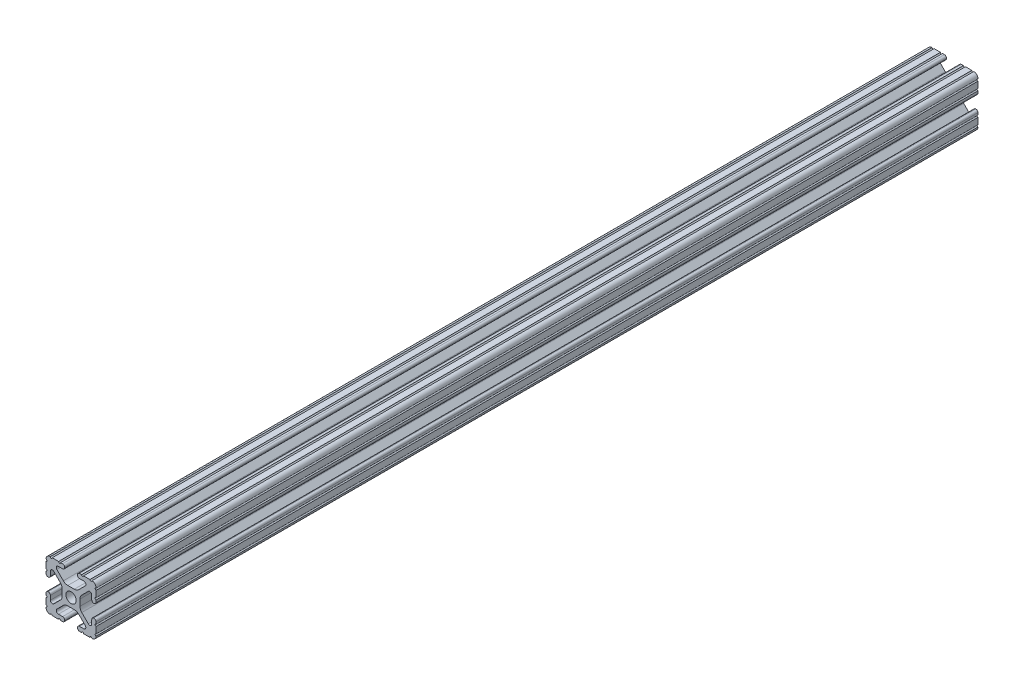
SolidWorks part; units mm, degrees
ref_plane "Front Plane" through (0, 0, 0) normal (0, 0, 1) x (1, 0, 0)
ref_plane "Top Plane" through (0, 0, 0) normal (0, 1, 0) x (1, 0, 0)
ref_plane "Right Plane" through (0, 0, 0) normal (1, 0, 0) x (0, 0, -1)
sketch "Sketch1" plane through (0, 0, 0) normal (0, 0, 1) x (1, 0, 0)
  line L88 (-7.1797, -8.6452) -> (-3.9523, -5.4237)
  line L89 (-1.7093, -4.4958) -> (1.7093, -4.4958)
  line L90 (3.9523, -5.4237) -> (7.1797, -8.6452)
  line L91 (6.4164, -10.4902) -> (4.2875, -10.4902)
  line L92 (3.2385, -11.5392) -> (3.2385, -11.651)
  line L93 (4.2875, -12.7) -> (5.3171, -12.7)
  line L94 (6.3331, -12.7) -> (9.5504, -12.7)
  line L95 (12.7, -9.5504) -> (12.7, -6.3331)
  line L96 (12.7, -5.3171) -> (12.7, -4.2875)
  line L97 (11.651, -3.2385) -> (11.5392, -3.2385)
  line L98 (10.4902, -4.2875) -> (10.4902, -6.4021)
  line L99 (8.7371, -7.1294) -> (5.441, -3.8408)
  line L100 (4.5085, -1.5932) -> (4.5085, 1.5932)
  line L101 (5.441, 3.8408) -> (8.7371, 7.1294)
  line L102 (10.4902, 6.4021) -> (10.4902, 4.2875)
  line L103 (11.5392, 3.2385) -> (11.651, 3.2385)
  line L104 (12.7, 4.2875) -> (12.7, 5.3171)
  line L105 (12.7, 6.3331) -> (12.7, 9.5504)
  line L106 (9.5504, 12.7) -> (6.3331, 12.7)
  line L107 (5.3171, 12.7) -> (4.2875, 12.7)
  line L108 (3.2385, 11.651) -> (3.2385, 11.5392)
  line L109 (4.2875, 10.4902) -> (6.4768, 10.4902)
  line L110 (7.207, 8.7244) -> (3.8983, 5.4232)
  line L111 (1.6558, 4.4958) -> (-1.6558, 4.4958)
  line L112 (-3.8983, 5.4232) -> (-7.207, 8.7244)
  line L113 (-6.4768, 10.4902) -> (-4.2875, 10.4902)
  line L114 (-3.2385, 11.5392) -> (-3.2385, 11.651)
  line L115 (-4.2875, 12.7) -> (-5.3171, 12.7)
  line L116 (-6.3331, 12.7) -> (-9.5504, 12.7)
  line L117 (-12.7, 9.5504) -> (-12.7, 6.3331)
  line L118 (-12.7, 5.3171) -> (-12.7, 4.2875)
  line L119 (-11.651, 3.2385) -> (-11.5392, 3.2385)
  line L120 (-10.4902, 4.2875) -> (-10.4902, 6.4021)
  line L121 (-8.7371, 7.1294) -> (-5.441, 3.8408)
  line L122 (-4.5085, 1.5932) -> (-4.5085, -1.5932)
  line L123 (-5.441, -3.8408) -> (-8.7371, -7.1294)
  line L124 (-10.4902, -6.4021) -> (-10.4902, -4.2875)
  line L125 (-11.5392, -3.2385) -> (-11.651, -3.2385)
  line L126 (-12.7, -4.2875) -> (-12.7, -5.3171)
  line L127 (-12.7, -6.3331) -> (-12.7, -9.5504)
  line L128 (-9.5504, -12.7) -> (-6.3331, -12.7)
  line L129 (-5.3171, -12.7) -> (-4.2875, -12.7)
  line L130 (-3.2385, -11.651) -> (-3.2385, -11.5392)
  line L131 (-4.2875, -10.4902) -> (-6.4164, -10.4902)
  circle A1 centre (0, 0) radius 2.6035
  arc A104 (-7.1797, -8.6452) -> (-6.4164, -10.4902) centre (-6.4164, -9.4098) ccw
  arc A105 (-1.7093, -4.4958) -> (-3.9523, -5.4237) centre (-1.7093, -7.6708) ccw
  arc A106 (3.9523, -5.4237) -> (1.7093, -4.4958) centre (1.7093, -7.6708) ccw
  arc A107 (6.4164, -10.4902) -> (7.1797, -8.6452) centre (6.4164, -9.4098) ccw
  arc A108 (4.2875, -10.4902) -> (3.2385, -11.5392) centre (4.2875, -11.5392) ccw
  arc A109 (3.2385, -11.651) -> (4.2875, -12.7) centre (4.2875, -11.651) ccw
  arc A110 (6.3331, -12.7) -> (5.3171, -12.7) centre (5.8251, -12.7) ccw
  arc A111 (10.5664, -12.6998) -> (9.5504, -12.7) centre (10.0584, -12.7) ccw
  arc A112 (10.5664, -12.6998) -> (12.6998, -10.5664) centre (10.5918, -10.5918) ccw
  arc A113 (12.7, -9.5504) -> (12.6998, -10.5664) centre (12.7, -10.0584) ccw
  arc A114 (12.7, -5.3171) -> (12.7, -6.3331) centre (12.7, -5.8251) ccw
  arc A115 (12.7, -4.2875) -> (11.651, -3.2385) centre (11.651, -4.2875) ccw
  arc A116 (11.5392, -3.2385) -> (10.4902, -4.2875) centre (11.5392, -4.2875) ccw
  arc A117 (8.7371, -7.1294) -> (10.4902, -6.4021) centre (9.4628, -6.4021) ccw
  arc A118 (4.5085, -1.5932) -> (5.441, -3.8408) centre (7.6835, -1.5932) ccw
  arc A119 (5.441, 3.8408) -> (4.5085, 1.5932) centre (7.6835, 1.5932) ccw
  arc A120 (10.4902, 6.4021) -> (8.7371, 7.1294) centre (9.4628, 6.4021) ccw
  arc A121 (10.4902, 4.2875) -> (11.5392, 3.2385) centre (11.5392, 4.2875) ccw
  arc A122 (11.651, 3.2385) -> (12.7, 4.2875) centre (11.651, 4.2875) ccw
  arc A123 (12.7, 6.3331) -> (12.7, 5.3171) centre (12.7, 5.8251) ccw
  arc A124 (12.6998, 10.5664) -> (12.7, 9.5504) centre (12.7, 10.0584) ccw
  arc A125 (12.6998, 10.5664) -> (10.5664, 12.6998) centre (10.5918, 10.5918) ccw
  arc A126 (9.5504, 12.7) -> (10.5664, 12.6998) centre (10.0584, 12.7) ccw
  arc A127 (5.3171, 12.7) -> (6.3331, 12.7) centre (5.8251, 12.7) ccw
  arc A128 (4.2875, 12.7) -> (3.2385, 11.651) centre (4.2875, 11.651) ccw
  arc A129 (3.2385, 11.5392) -> (4.2875, 10.4902) centre (4.2875, 11.5392) ccw
  arc A130 (7.207, 8.7244) -> (6.4768, 10.4902) centre (6.4768, 9.4563) ccw
  arc A131 (1.6558, 4.4958) -> (3.8983, 5.4232) centre (1.6558, 7.6708) ccw
  arc A132 (-3.8983, 5.4232) -> (-1.6558, 4.4958) centre (-1.6558, 7.6708) ccw
  arc A133 (-6.4768, 10.4902) -> (-7.207, 8.7244) centre (-6.4768, 9.4563) ccw
  arc A134 (-4.2875, 10.4902) -> (-3.2385, 11.5392) centre (-4.2875, 11.5392) ccw
  arc A135 (-3.2385, 11.651) -> (-4.2875, 12.7) centre (-4.2875, 11.651) ccw
  arc A136 (-6.3331, 12.7) -> (-5.3171, 12.7) centre (-5.8251, 12.7) ccw
  arc A137 (-10.5664, 12.6998) -> (-9.5504, 12.7) centre (-10.0584, 12.7) ccw
  arc A138 (-10.5664, 12.6998) -> (-12.6998, 10.5664) centre (-10.5918, 10.5918) ccw
  arc A139 (-12.7, 9.5504) -> (-12.6998, 10.5664) centre (-12.7, 10.0584) ccw
  arc A140 (-12.7, 5.3171) -> (-12.7, 6.3331) centre (-12.7, 5.8251) ccw
  arc A141 (-12.7, 4.2875) -> (-11.651, 3.2385) centre (-11.651, 4.2875) ccw
  arc A142 (-11.5392, 3.2385) -> (-10.4902, 4.2875) centre (-11.5392, 4.2875) ccw
  arc A143 (-8.7371, 7.1294) -> (-10.4902, 6.4021) centre (-9.4628, 6.4021) ccw
  arc A144 (-4.5085, 1.5932) -> (-5.441, 3.8408) centre (-7.6835, 1.5932) ccw
  arc A145 (-5.441, -3.8408) -> (-4.5085, -1.5932) centre (-7.6835, -1.5932) ccw
  arc A146 (-10.4902, -6.4021) -> (-8.7371, -7.1294) centre (-9.4628, -6.4021) ccw
  arc A147 (-10.4902, -4.2875) -> (-11.5392, -3.2385) centre (-11.5392, -4.2875) ccw
  arc A148 (-11.651, -3.2385) -> (-12.7, -4.2875) centre (-11.651, -4.2875) ccw
  arc A149 (-12.7, -6.3331) -> (-12.7, -5.3171) centre (-12.7, -5.8251) ccw
  arc A150 (-12.6998, -10.5664) -> (-12.7, -9.5504) centre (-12.7, -10.0584) ccw
  arc A151 (-12.6998, -10.5664) -> (-10.5664, -12.6998) centre (-10.5918, -10.5918) ccw
  arc A152 (-9.5504, -12.7) -> (-10.5664, -12.6998) centre (-10.0584, -12.7) ccw
  arc A153 (-5.3171, -12.7) -> (-6.3331, -12.7) centre (-5.8251, -12.7) ccw
  arc A154 (-4.2875, -12.7) -> (-3.2385, -11.651) centre (-4.2875, -11.651) ccw
  arc A155 (-3.2385, -11.5392) -> (-4.2875, -10.4902) centre (-4.2875, -11.5392) ccw
extrude "Boss-Extrude1" add sketch "Sketch1" along normal mid plane 447.04
ref_plane "Plane1" through (0, 0, 0) normal (0, -1, 0) x (-1, 0, 0)
